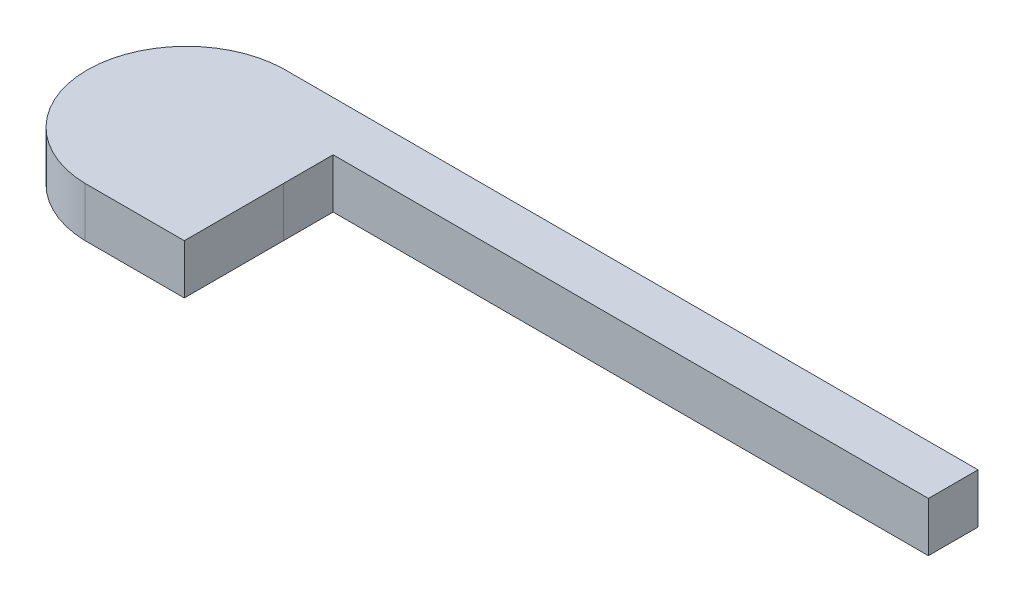
SolidWorks part; units mm, degrees
ref_plane "Front Plane" through (0, 0, 0) normal (0, 0, 1) x (1, 0, 0)
ref_plane "Top Plane" through (0, 0, 0) normal (0, 1, 0) x (1, 0, 0)
ref_plane "Right Plane" through (0, 0, 0) normal (1, 0, 0) x (0, 0, -1)
sketch "Sketch2" plane through (0, 0, 0) normal (0, 1, 0) x (1, 0, 0)
  line L1 (-50.8, 12.7) -> (50.8, 12.7)
  line L2 (-50.8, 12.7) -> (-50.8, -12.7)
  line L3 (-50.8, -12.7) -> (50.8, -12.7)
  line L4 (50.8, 12.7) -> (50.8, -12.7)
  line L5 (-50.8, 12.7) -> (50.8, -12.7) construction
  line L6 (-50.8, -12.7) -> (50.8, 12.7) construction
  point P0 (0, 0)
extrude "Boss-Extrude1" add sketch "Sketch2" along normal blind 6.35
sketch "Sketch3" plane through (0, 0, 0) normal (0, -1, 0) x (1, 0, 0)
  circle A0 centre (-38.1, 0) radius 6.35
extrude "Cut-Extrude1" cut sketch "Sketch3" against normal blind 3.81
sketch "Sketch4" plane through (0, 6.35, 0) normal (0, 1, 0) x (1, 0, 0)
  line L0 (-25.4, 0) -> (-25.4, -12.7)
  line L1 (-50.8, -12.7) -> (50.8, -12.7) construction
  line L2 (-25.4, 0) -> (-25.4, 6.35)
  line L3 (-25.4, 6.35) -> (50.8, 6.35)
  line L4 (50.8, -12.7) -> (50.8, 12.7) construction
extrude "Cut-Extrude2" cut sketch "Sketch4" against normal blind 6.35 and the other way through all flip side to cut
sketch "Sketch5" plane through (0, 6.35, 0) normal (0, 1, 0) x (1, 0, 0)
  line L0 (-50.8, -12.7) -> (-25.4, -12.7) construction
  line L1 (50.8, 12.7) -> (-50.8, 12.7) construction
  arc A0 (-38.1, -12.7) -> (-38.1, 12.7) centre (-37.8434, 0) cw
extrude "Cut-Extrude3" cut sketch "Sketch5" against normal blind 6.35 and the other way through all
